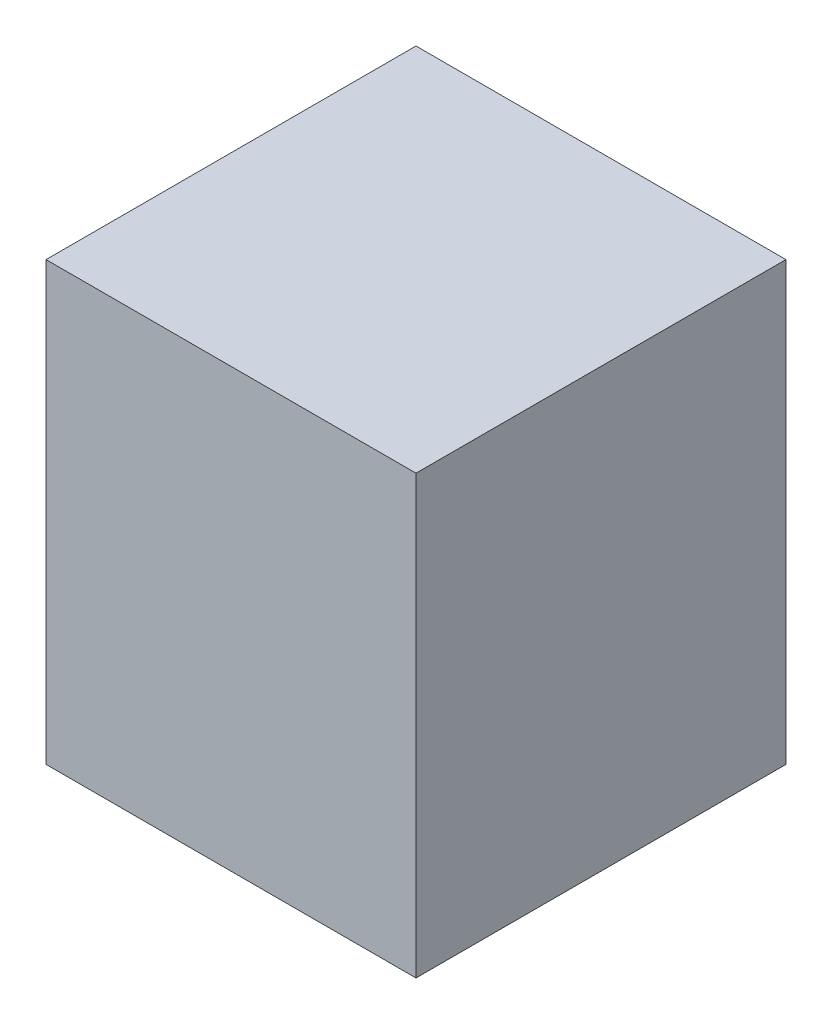
SolidWorks part; units mm, degrees
ref_plane "Front Plane" through (0, 0, 0) normal (0, 0, 1) x (1, 0, 0)
ref_plane "Top Plane" through (0, 0, 0) normal (0, 1, 0) x (1, 0, 0)
ref_plane "Right Plane" through (0, 0, 0) normal (1, 0, 0) x (0, 0, -1)
sketch "Sketch1" plane through (0, 0, 0) normal (0, 0, 1) x (1, 0, 0)
  line L1 (-27.5, 32.5) -> (27.5, 32.5)
  line L2 (-27.5, 32.5) -> (-27.5, -32.5)
  line L3 (-27.5, -32.5) -> (27.5, -32.5)
  line L4 (27.5, 32.5) -> (27.5, -32.5)
  line L5 (-27.5, 32.5) -> (27.5, -32.5) construction
  line L6 (-27.5, -32.5) -> (27.5, 32.5) construction
  point P0 (0, 0)
  point P5 (0, 0)
  point P6 (0, 0)
  dimension "D1" = 55
  dimension "D2" = 65
extrude "Boss-Extrude1" add sketch "Sketch1" along normal blind 55 and the other way blind 10 draft 45
